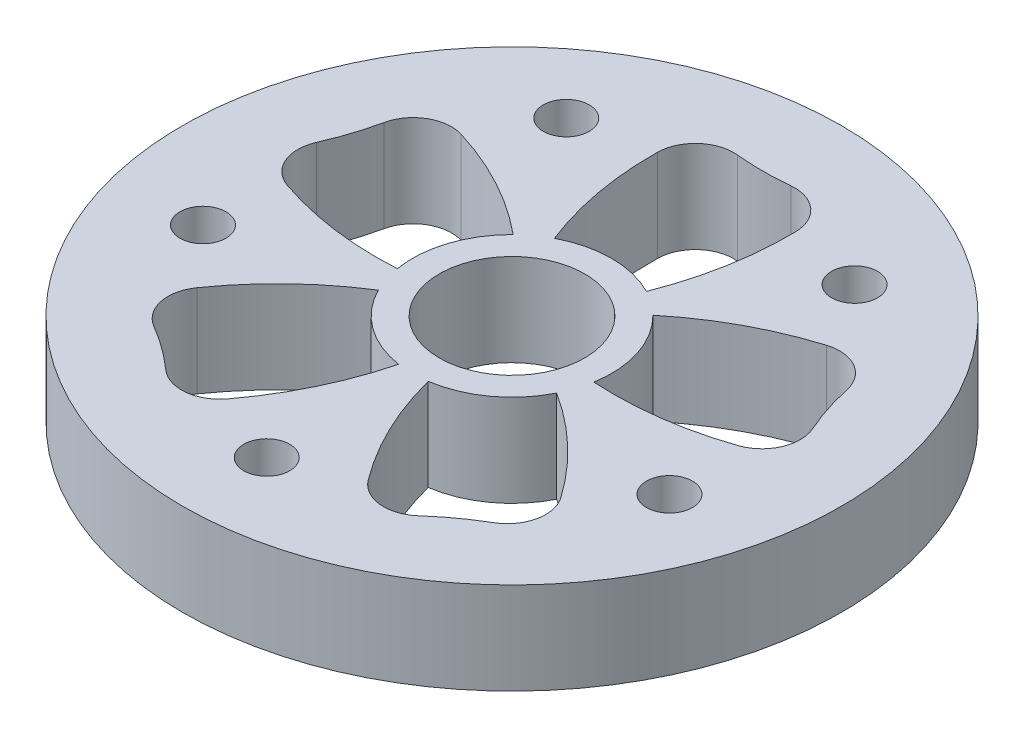
SolidWorks part; units mm, degrees
ref_plane "前视基准面" through (0, 0, 0) normal (0, 0, 1) x (1, 0, 0)
ref_plane "上视基准面" through (0, 0, 0) normal (0, 1, 0) x (1, 0, 0)
ref_plane "右视基准面" through (0, 0, 0) normal (1, 0, 0) x (0, 0, -1)
other "Configuration Table"
sketch "草图1" plane through (0, 0, 0) normal (0, 1, 0) x (1, 0, 0)
  line L0 (0, 47.7141) -> (0, -57.7214) construction
  circle A0 centre (0, 0) radius 43
  circle A1 centre (0, -32) radius 3
  circle A2 centre (-30.4338, -9.8885) radius 3
  circle A3 centre (-18.8091, 25.8885) radius 3
  circle A4 centre (18.8091, 25.8885) radius 3
  circle A5 centre (30.4338, -9.8885) radius 3
  point P17 (0, 0)
  dimension "D1" = 86
  dimension "D3" = 6
  dimension "D2" = 32
  dimension "D4" = 5
extrude "凸台-拉伸1" add sketch "草图1" along normal blind 12
sketch "草图2" plane through (0, 12, 0) normal (0, 1, 0) x (1, 0, 0)
  line L0 (0, 30.6791) -> (0, -25.7748) construction
  circle A0 centre (0, 0) radius 9.5
  arc A1 (6, 11.5326) -> (-6, 11.5326) centre (0, 0) ccw
  arc A2 (-6, 11.5326) -> (-8.9994, 28) centre (33.9953, 27.3242) cw
  arc A3 (-8.9994, 28) -> (-3.5, 32.8964) centre (-4, 27.9214) cw
  arc A4 (-3.5, 32.8964) -> (3.5, 32.8964) centre (0, 67.7209) ccw
  arc A5 (6, 11.5326) -> (8.9994, 28) centre (-33.9953, 27.3242) ccw
  arc A6 (8.9994, 28) -> (3.5, 32.8964) centre (4, 27.9214) ccw
  arc A7 (12.8222, -2.1426) -> (9.114, 9.2701) centre (0, 0) ccw
  arc A8 (9.114, 9.2701) -> (23.8486, 17.2114) centre (36.492, -23.8878) cw
  arc A9 (23.8486, 17.2114) -> (30.2047, 13.4942) centre (25.3188, 12.4324) cw
  arc A10 (30.2047, 13.4942) -> (32.3679, 6.8368) centre (64.4064, 20.9269) ccw
  arc A11 (29.4105, 0.0936) -> (32.3679, 6.8368) centre (27.7909, 4.824) ccw
  arc A12 (12.8222, -2.1426) -> (29.4105, 0.0936) centre (15.4817, 40.7751) ccw
  arc A13 (1.9246, -12.8568) -> (11.6328, -5.8033) centre (0, 0) ccw
  arc A14 (11.6328, -5.8033) -> (23.7386, -17.3628) centre (-11.442, -42.0877) cw
  arc A15 (23.7386, -17.3628) -> (22.1676, -24.5565) centre (19.6479, -20.2378) cw
  arc A16 (22.1676, -24.5565) -> (16.5044, -28.671) centre (39.8054, -54.7874) ccw
  arc A17 (9.1773, -27.9422) -> (16.5044, -28.671) centre (13.1757, -24.94) ccw
  arc A18 (1.9246, -12.8568) -> (9.1773, -27.9422) centre (43.5635, -2.1238) ccw
  arc A19 (-11.6328, -5.8033) -> (-1.9246, -12.8568) centre (0, 0) ccw
  arc A20 (-1.9246, -12.8568) -> (-9.1773, -27.9422) centre (-43.5635, -2.1238) cw
  arc A21 (-9.1773, -27.9422) -> (-16.5044, -28.671) centre (-13.1757, -24.94) cw
  arc A22 (-16.5044, -28.671) -> (-22.1676, -24.5565) centre (-39.8054, -54.7874) ccw
  arc A23 (-23.7386, -17.3628) -> (-22.1676, -24.5565) centre (-19.6479, -20.2378) ccw
  arc A24 (-11.6328, -5.8033) -> (-23.7386, -17.3628) centre (11.442, -42.0877) ccw
  arc A25 (-9.114, 9.2701) -> (-12.8222, -2.1426) centre (0, 0) ccw
  arc A26 (-12.8222, -2.1426) -> (-29.4105, 0.0936) centre (-15.4817, 40.7751) cw
  arc A27 (-29.4105, 0.0936) -> (-32.3679, 6.8368) centre (-27.7909, 4.824) cw
  arc A28 (-32.3679, 6.8368) -> (-30.2047, 13.4942) centre (-64.4064, 20.9269) ccw
  arc A29 (-23.8486, 17.2114) -> (-30.2047, 13.4942) centre (-25.3188, 12.4324) ccw
  arc A30 (-9.114, 9.2701) -> (-23.8486, 17.2114) centre (-36.492, -23.8878) ccw
  point P62 (0, 0)
  dimension "D1" = 19
  dimension "D2" = 26
  dimension "D3" = 5
  dimension "D4" = 43
  dimension "D5" = 7
  dimension "D6" = 28
  dimension "D7" = 8
  dimension "D8" = 12
  dimension "D9" = 5
extrude "切除-拉伸1" cut sketch "草图2" against normal through all
